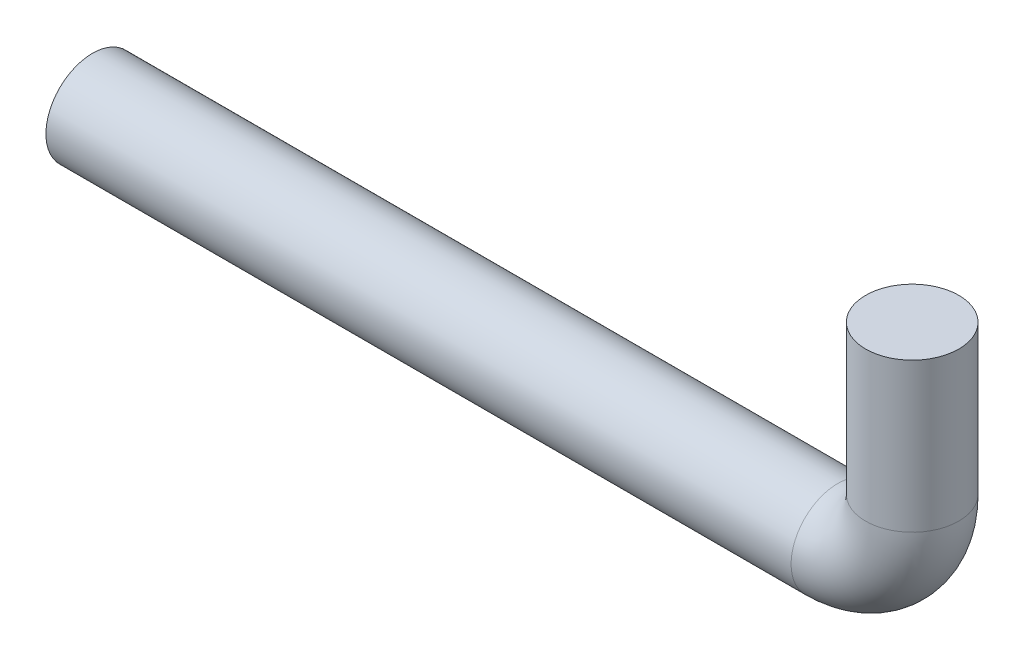
SolidWorks part; units mm, degrees
ref_plane "Front Plane" through (0, 0, 0) normal (0, 0, 1) x (1, 0, 0)
ref_plane "Top Plane" through (0, 0, 0) normal (0, 1, 0) x (1, 0, 0)
ref_plane "Right Plane" through (0, 0, 0) normal (1, 0, 0) x (0, 0, -1)
sketch "Sketch2" plane through (0, 0, 0) normal (0, 0, 1) x (1, 0, 0)
  line L0 (0, 0) -> (12.7, 0)
  line L1 (13.97, 1.27) -> (13.97, 3.81)
  arc A0 (12.7, 0) -> (13.97, 1.27) centre (12.7, 1.27) ccw
  dimension "D3" = 1.27
  dimension "D1" = 2.54
  dimension "D2" = 12.7
sketch "Sketch1" plane through (0, 0, 0) normal (1, 0, 0) x (0, 0, -1)
  circle A0 centre (0, 0) radius 0.7937
  dimension "D1" = 1.5875
sweep "Sweep1" add profiles "Sketch1" path "Sketch2"
